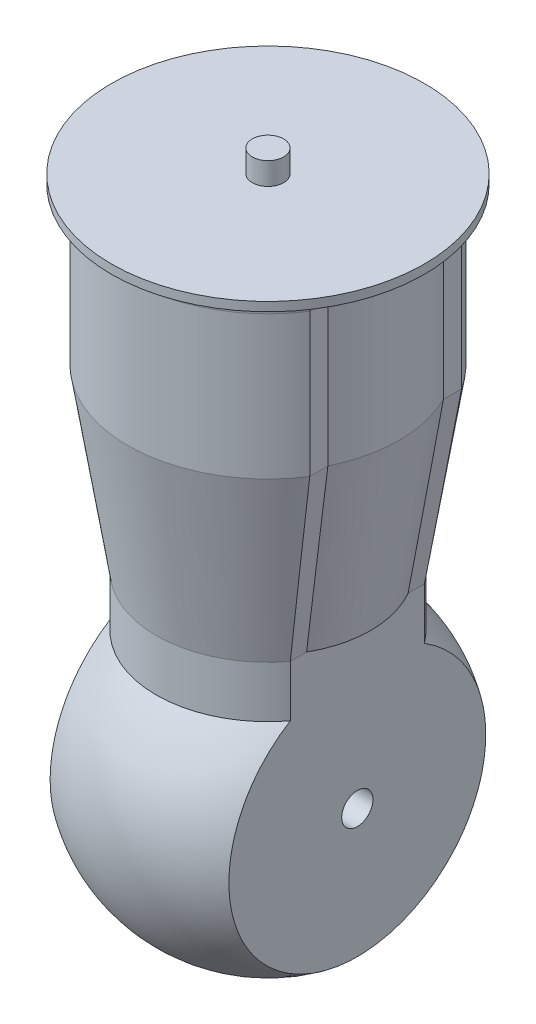
SolidWorks part; units mm, degrees
ref_plane "Front Plane" through (0, 0, 0) normal (0, 0, 1) x (1, 0, 0)
ref_plane "Top Plane" through (0, 0, 0) normal (0, 1, 0) x (1, 0, 0)
ref_plane "Right Plane" through (0, 0, 0) normal (1, 0, 0) x (0, 0, -1)
sketch "Sketch1" plane through (0, 0, 0) normal (0, 1, 0) x (1, 0, 0)
  line L0 (0, 35) -> (0, -35) construction
  line L1 (0, 35) -> (0, -35)
  arc A0 (0, -35) -> (0, 35) centre (0, 0) ccw
  dimension "D1" = 70
revolve "Revolve2" add sketch "Sketch1" angle 360 about L0
sketch "Sketch2" plane through (0, 0, 0) normal (0, 1, 0) x (1, 0, 0)
  line L2 (-20, -28.7228) -> (-20, 28.7228)
  line L4 (20, -28.7228) -> (20, 28.7228)
  line L5 (-20, -35) -> (20, 35) construction
  line L6 (-20, 35) -> (20, -35) construction
  arc A0 (20, 28.7228) -> (-20, 28.7228) centre (0, 0) ccw
  arc A1 (-20, -28.7228) -> (20, -28.7228) centre (0, 0) ccw
  dimension "D1" = 40
extrude "Cut-Extrude1" cut sketch "Sketch2" against normal up to next and the other way up to next flip side to cut
sketch "Sketch3" plane through (0, 0, 0) normal (0, 1, 0) x (1, 0, 0)
  line L4 (20, -28.7228) -> (20, 28.7228) construction
  line L6 (-20, 15) -> (-20, -15)
  line L8 (20, 15) -> (20, -15)
  line L9 (-20, 26.2775) -> (20, -26.2775) construction
  line L10 (-20, -26.2775) -> (20, 26.2775) construction
  arc A3 (20, 15) -> (-20, 15) centre (0, 0) ccw
  arc A4 (-20, -15) -> (20, -15) centre (0, 0) ccw
  arc A6 (-20, -28.7228) -> (20, -28.7228) centre (0, 0) ccw construction
  dimension "D1" = 50
  dimension "D2" = 10
extrude "Boss-Extrude1" add sketch "Sketch3" along normal blind 36
sketch "Sketch4" plane through (-20, 0, 0) normal (-1, 0, 0) x (0, 0, 1)
  circle A0 centre (0, 0) radius 3.5
  dimension "D1" = 7
extrude "Cut-Extrude2" cut sketch "Sketch4" against normal blind 5
pattern_linear "LPattern1" count 2 spacing 35 along (1, 0, 0) of "Cut-Extrude2"
sketch "Sketch5" plane through (0, 36, 0) normal (0, 1, 0) x (1, 0, 0)
  line L0 (-20, 15) -> (-20, 11.3578)
  line L1 (-20, 15) -> (-20, -15) construction
  line L2 (-20, -15) -> (-20, -11.3578)
  line L3 (20, 15) -> (20, 11.3578)
  line L4 (20, -11.3578) -> (20, -15)
  arc A0 (-20, -15) -> (20, -15) centre (0, 0) ccw
  arc A1 (20, -11.3578) -> (20, 11.3578) centre (0, 0) ccw
  arc A2 (20, 15) -> (-20, 15) centre (0, 0) ccw
  arc A3 (-20, 11.3578) -> (-20, -11.3578) centre (0, 0) ccw
  dimension "D2" = 46
extrude "Boss-Extrude2" add sketch "Sketch5" along normal blind 40 draft 9 draft outward yes
sketch "Sketch9" plane through (0, 76, 0) normal (0, 1, 0) x (1, 0, 0)
  line L4 (26.3354, 12.9233) -> (26.3354, 16.981)
  line L5 (-26.3354, 16.981) -> (-26.3354, 12.9233)
  line L6 (-26.3354, -12.9233) -> (-26.3354, -16.981)
  line L7 (26.3354, -16.981) -> (26.3354, -12.9233)
  line L8 (26.3354, 12.9233) -> (26.3354, 16.981)
  line L9 (-26.3354, 16.981) -> (-26.3354, 12.9233)
  line L10 (-26.3354, -12.9233) -> (-26.3354, -16.981)
  line L11 (26.3354, -16.981) -> (26.3354, -12.9233)
  arc A4 (26.3354, -12.9233) -> (26.3354, 12.9233) centre (0, 0) ccw
  arc A5 (26.3354, 16.981) -> (-26.3354, 16.981) centre (0, 0) ccw
  arc A6 (-26.3354, 12.9233) -> (-26.3354, -12.9233) centre (0, 0) ccw
  arc A7 (-26.3354, -16.981) -> (26.3354, -16.981) centre (0, 0) ccw
  arc A8 (26.3354, -12.9233) -> (26.3354, 12.9233) centre (0, 0) ccw
  arc A9 (26.3354, 16.981) -> (-26.3354, 16.981) centre (0, 0) ccw
  arc A10 (-26.3354, 12.9233) -> (-26.3354, -12.9233) centre (0, 0) ccw
  arc A11 (-26.3354, -16.981) -> (26.3354, -16.981) centre (0, 0) ccw
  dimension "D1" = 0
extrude "Boss-Extrude6" add sketch "Sketch9" along normal blind 35
sketch "Sketch10" plane through (0, 111, 0) normal (0, 1, 0) x (1, 0, 0)
  circle A0 centre (0, 0) radius 35
  dimension "D1" = 70
extrude "Boss-Extrude7" add sketch "Sketch10" along normal blind 2
fillet "Fillet5" radius 3 8 edges at (26.3354, 111, 14.9522) (29.3354, 111, 0) (26.3354, 111, -14.9522) (-26.3354, 111, 14.9522) (0, 111, 31.3354) (-29.3354, 111, 0) (-26.3354, 111, -14.9522) (0, 111, -31.3354)
sketch "Sketch11" plane through (0, 113, 0) normal (0, 1, 0) x (1, 0, 0)
  circle A0 centre (0, 0) radius 3.5
  dimension "D1" = 7
extrude "Boss-Extrude8" add sketch "Sketch11" along normal blind 5
